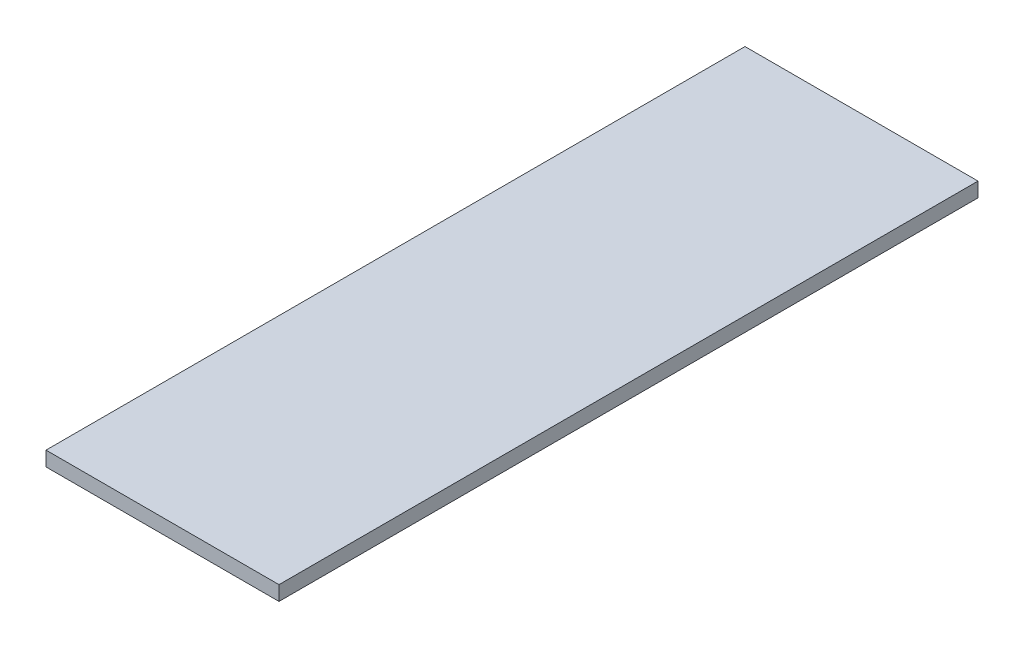
SolidWorks part; units mm, degrees
material "Rubber"
ref_plane "Front" through (0, 0, 0) normal (0, 0, 1) x (1, 0, 0)
ref_plane "Top" through (0, 0, 0) normal (0, 1, 0) x (1, 0, 0)
ref_plane "Right" through (0, 0, 0) normal (1, 0, 0) x (0, 0, -1)
sketch "Sketch1" plane through (0, 0, 0) normal (0, 1, 0) x (1, 0, 0)
  line L1 (-6.35, 19.05) -> (6.35, 19.05)
  line L2 (-6.35, 19.05) -> (-6.35, -19.05)
  line L3 (-6.35, -19.05) -> (6.35, -19.05)
  line L4 (6.35, 19.05) -> (6.35, -19.05)
  line L5 (-6.35, 19.05) -> (6.35, -19.05) construction
  line L6 (-6.35, -19.05) -> (6.35, 19.05) construction
  point P0 (0, 0)
  dimension "D1" = 12.7
  dimension "D2" = 38.1
extrude "Boss-Extrude1" add sketch "Sketch1" along normal blind 0.7937
